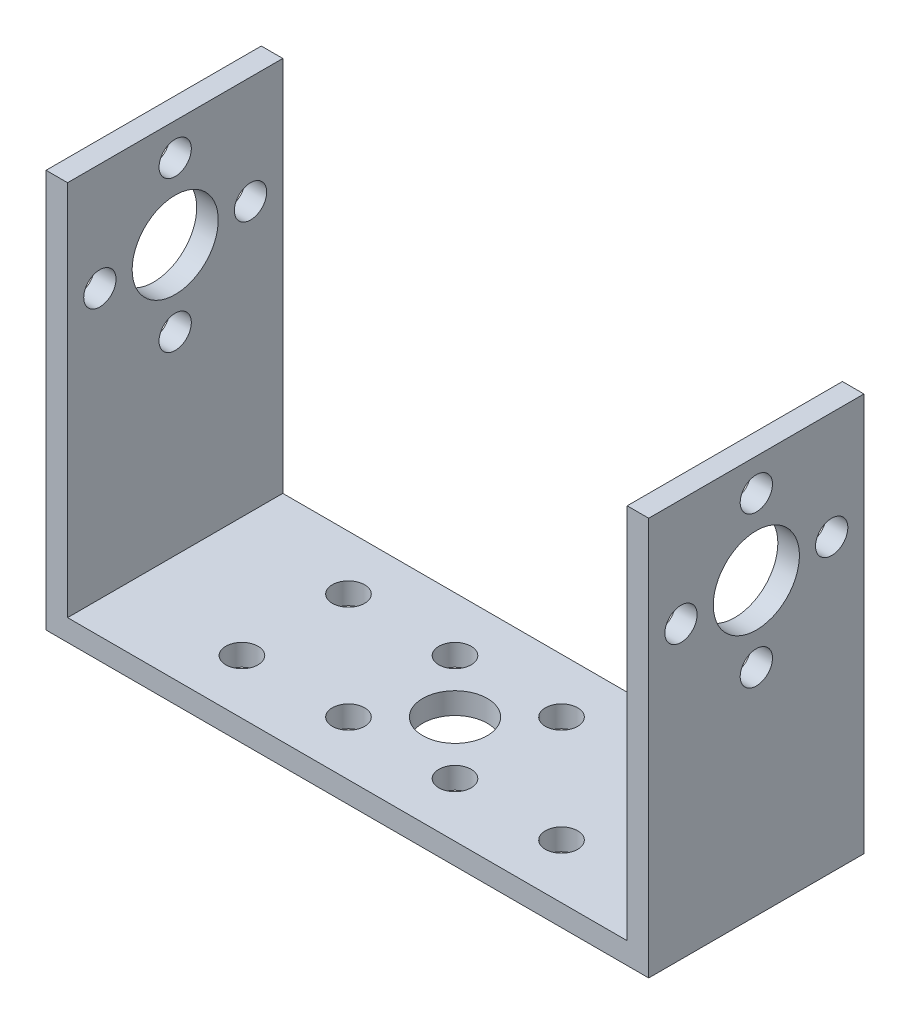
SolidWorks part; units mm, degrees
ref_plane "Front Plane" through (0, 0, 0) normal (0, 0, 1) x (1, 0, 0)
ref_plane "Top Plane" through (0, 0, 0) normal (0, 1, 0) x (1, 0, 0)
ref_plane "Right Plane" through (0, 0, 0) normal (1, 0, 0) x (0, 0, -1)
sketch "Sketch1" plane through (0, 0, 0) normal (0, 1, 0) x (1, 0, 0)
  line L1 (-2.124, -1.0465) -> (53.876, -1.0465)
  line L2 (-2.124, -1.0465) -> (-2.124, 18.9535)
  line L3 (-2.124, 18.9535) -> (53.876, 18.9535)
  line L4 (53.876, -1.0465) -> (53.876, 18.9535)
  dimension "D1" = 20
  dimension "D2" = 56
extrude "Boss-Extrude1" add sketch "Sketch1" along normal blind 2
sketch "Sketch2" plane through (0, 2, 0) normal (0, 1, 0) x (1, 0, 0)
  line L0 (-2.124, -1.0465) -> (53.876, -1.0465) construction
  line L1 (-2.124, 18.9535) -> (-0.124, 18.9535)
  line L2 (-2.124, 18.9535) -> (-2.124, -1.0465)
  line L3 (-2.124, -1.0465) -> (-0.124, -1.0465)
  line L4 (-0.124, 18.9535) -> (-0.124, -1.0465)
  line L6 (53.876, 18.9535) -> (51.876, 18.9535)
  line L7 (53.876, 18.9535) -> (53.876, -1.0465)
  line L8 (53.876, -1.0465) -> (51.876, -1.0465)
  line L9 (51.876, 18.9535) -> (51.876, -1.0465)
  dimension "D1" = 2
  dimension "D2" = 2
extrude "Boss-Extrude2" add sketch "Sketch2" along normal blind 35
sketch "Sketch3" plane through (-2.124, 0, 0) normal (-1, 0, 0) x (0, 0, 1)
  line L0 (-18.9535, 37) -> (-18.9535, 0) construction
  line L1 (-18.9535, 37) -> (1.0465, 37) construction
  circle A0 centre (-8.9535, 27) radius 4
  circle A1 centre (-15.9535, 27) radius 1.5
  circle A2 centre (-1.9535, 27) radius 1.5
  circle A3 centre (-8.9535, 34) radius 1.5
  circle A4 centre (-8.9535, 20) radius 1.5
  dimension "D1" = 8
  dimension "D4" = 3
  dimension "D5" = 3
  dimension "D6" = 3
  dimension "D7" = 3
  dimension "D2" = 10
  dimension "D3" = 10
  dimension "D8" = 3
  dimension "D9" = 7
  dimension "D10" = 7
  dimension "D11" = 7
extrude "Cut-Extrude1" cut sketch "Sketch3" against normal through all
sketch "Sketch4" plane through (0, 2, 0) normal (0, 1, 0) x (1, 0, 0)
  line L0 (-2.124, 18.9535) -> (-2.124, -1.0465) construction
  line L1 (-0.124, -1.0465) -> (51.876, -1.0465) construction
  circle A0 centre (30.8255, 4.004) radius 1.5
  circle A1 centre (20.9265, 4.004) radius 1.5
  circle A2 centre (30.8255, 13.903) radius 1.5
  circle A3 centre (20.9265, 13.903) radius 1.5
  circle A4 centre (25.876, 8.9535) radius 3
  circle A5 centre (40.7245, 4.004) radius 1.5
  circle A6 centre (40.7245, 13.903) radius 1.5
  circle A7 centre (11.0275, 13.903) radius 1.5
  circle A8 centre (11.0275, 4.004) radius 1.5
  dimension "D1" = 3
  dimension "D2" = 3
  dimension "D3" = 3
  dimension "D4" = 3
  dimension "D11" = 6
  dimension "D12" = 28
  dimension "D16" = 3
  dimension "D17" = 3
  dimension "D18" = 3
  dimension "D19" = 3
  dimension "D22" = 9.899
  dimension "D5" = 9.899
  dimension "D6" = 9.899
  dimension "D7" = 0
  dimension "D8" = 0
  dimension "D9" = 0
  dimension "D10" = 0
  dimension "D13" = 10
  dimension "D14" = 4.9495
  dimension "D15" = 4.9495
  dimension "D20" = 0
  dimension "D21" = 0
  dimension "D23" = 9.899
extrude "Cut-Extrude2" cut sketch "Sketch4" against normal through all
